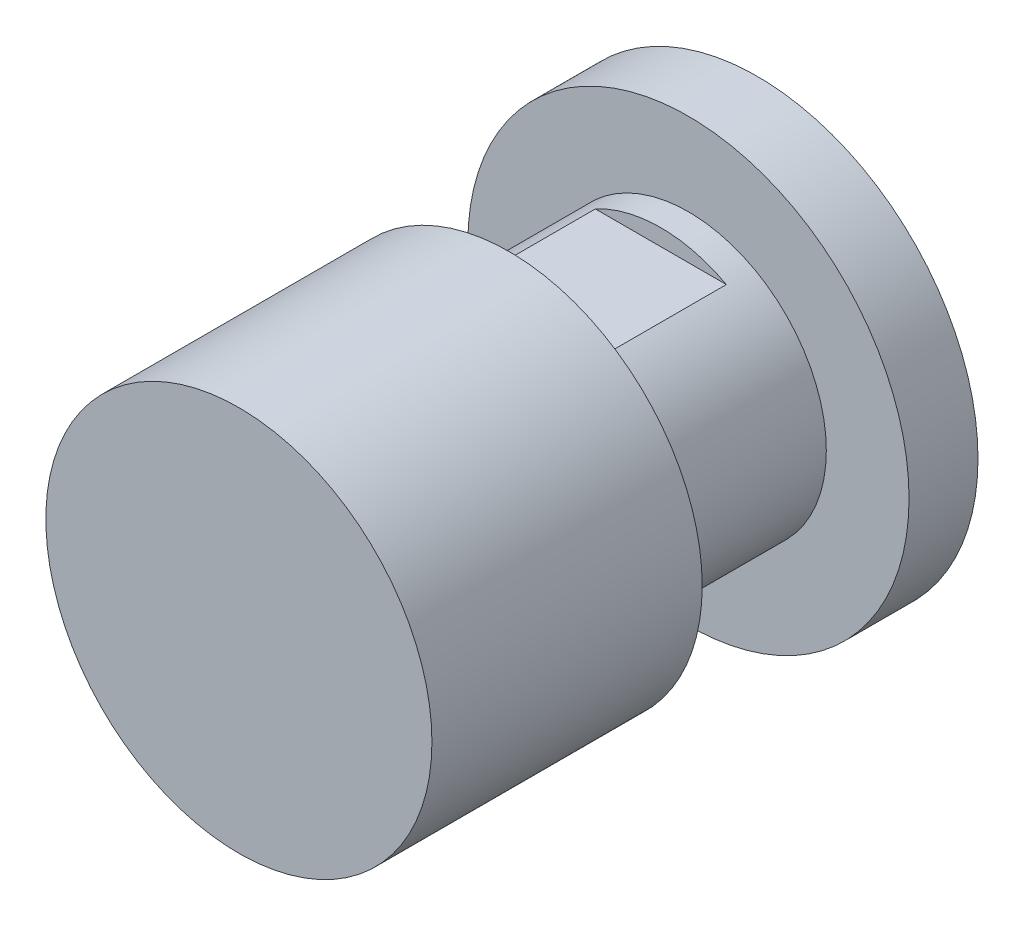
SolidWorks part; units mm, degrees
ref_plane "Front Plane" through (0, 0, 0) normal (0, 0, 1) x (1, 0, 0)
ref_plane "Top Plane" through (0, 0, 0) normal (0, 1, 0) x (1, 0, 0)
ref_plane "Right Plane" through (0, 0, 0) normal (1, 0, 0) x (0, 0, -1)
sketch "Sketch1" plane through (0, 0, 0) normal (0, 0, 1) x (1, 0, 0)
  circle A0 centre (0, 0) radius 16
  dimension "D1" = 32
extrude "Boss-Extrude1" add sketch "Sketch1" along normal blind 5
sketch "Sketch2" plane through (0, 0, 5) normal (0, 0, 1) x (1, 0, 0)
  circle A0 centre (0, 0) radius 10
  dimension "D1" = 20
extrude "Boss-Extrude2" add sketch "Sketch2" along normal blind 24
ref_plane "Plane1" through (0, 0, 7) normal (0, 0, 1) x (1, 0, 0)
sketch "Sketch4" plane through (0, 0, 7) normal (0, 0, 1) x (1, 0, 0)
  line L1 (-12, -8.8) -> (12, -8.8)
  line L2 (-12, -8.8) -> (-12, 8.8)
  line L3 (-12, 8.8) -> (12, 8.8)
  line L4 (12, -8.8) -> (12, 8.8)
  line L5 (-12, -8.8) -> (12, 8.8) construction
  line L6 (-12, 8.8) -> (12, -8.8) construction
  point P0 (0, 0)
  dimension "D1" = 17.6
  dimension "D2" = 24
extrude "Cut-Extrude1" cut sketch "Sketch4" along normal blind 9 flip side to cut
ref_plane "Plane2" through (0, 0, 18) normal (0, 0, 1) x (1, 0, 0)
sketch "Sketch5" plane through (0, 0, 18) normal (0, 0, 1) x (1, 0, 0)
  circle A0 centre (0, 0) radius 14
  dimension "D1" = 28
extrude "Boss-Extrude3" add sketch "Sketch5" along normal blind 19.6
